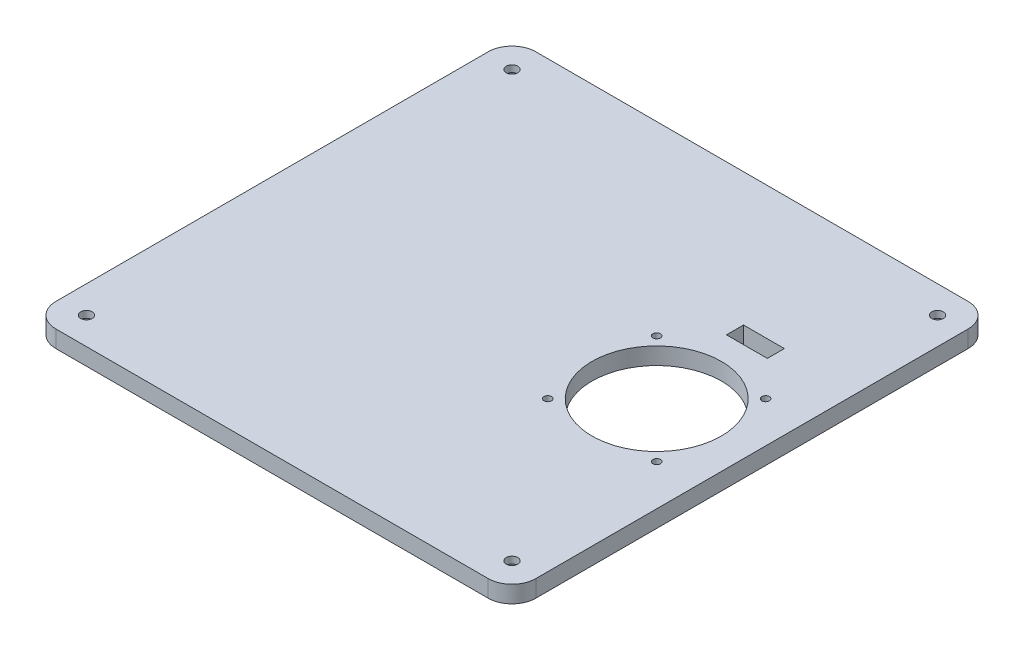
SolidWorks part; units mm, degrees
ref_plane "Front Plane" through (0, 0, 0) normal (0, 0, 1) x (1, 0, 0)
ref_plane "Top Plane" through (0, 0, 0) normal (0, 1, 0) x (1, 0, 0)
ref_plane "Right Plane" through (0, 0, 0) normal (1, 0, 0) x (0, 0, -1)
sketch "Sketch1" plane through (0, 0, 0) normal (0, 1, 0) x (1, 0, 0)
  line L1 (-70.5, 70.5) -> (70.5, 70.5)
  line L2 (-70.5, 70.5) -> (-70.5, -70.5)
  line L3 (-70.5, -70.5) -> (70.5, -70.5)
  line L4 (70.5, 70.5) -> (70.5, -70.5)
  line L5 (0, -70.5) -> (0, 70.5) construction
  line L6 (-70.5, 0) -> (70.5, 0) construction
  point P0 (0, 0)
  dimension "D1" = 141
  dimension "D2" = 141
extrude "Boss-Extrude1" add sketch "Sketch1" along normal blind 5
sketch "Sketch3" plane through (0, 5, 0) normal (0, 1, 0) x (1, 0, 0)
  line L1 (26.5, 16) -> (58.5, 16) construction
  line L2 (26.5, 16) -> (26.5, -16) construction
  line L3 (26.5, -16) -> (58.5, -16) construction
  line L4 (58.5, 16) -> (58.5, -16) construction
  line L5 (70.5, -70.5) -> (70.5, 70.5) construction
  circle A0 centre (26.5, 16) radius 1.1
  circle A1 centre (58.5, 16) radius 1.1
  circle A2 centre (58.5, -16) radius 1.1
  circle A3 centre (26.5, -16) radius 1.1
  point P8 (26.5, 0)
  dimension "D1" = 2.2
  dimension "D2" = 32
  dimension "D3" = 32
  dimension "D4" = 12
extrude "Cut-Extrude1" cut sketch "Sketch3" against normal up to next
hole_wizard "CBORE for M3 SHCS1" positions "3DSketch1" profile "Sketch8" counterbore size "M3" standard "ANSI Metric" end condition through all
sketch3d "3DSketch1"
  line L0 (-70.5, 0, -70.5) -> (-70.5, 0, 70.5) construction
  line L1 (-70.5, 0, 70.5) -> (70.5, 0, 70.5) construction
  point P15 (-62.5, 0, 62.5)
  point P22 (-62.5, 0, -62.5)
  point P25 (62.5, 0, -62.5)
  point P26 (62.5, 0, 62.5)
  dimension "D1" = 8
  dimension "D2" = 8
sketch "Sketch8" plane through (-62.5, 0, 62.5) normal (1, 0, 0) x (0, 0, -1)
  line L0 (0, 0) -> (0, 5)
  line L1 (0, 5) -> (1.7, 5)
  line L3 (1.7, 5) -> (1.7, 3)
  line L4 (1.7, 3) -> (3.25, 3)
  line L5 (3.25, 3) -> (3.25, 0)
  line L7 (3.25, 0) -> (0, 0)
  line L11 (0, -6.35) -> (0, 107.95) construction
  dimension "Thru Hole Dia." = 3.4
  dimension "Thru Hole Depth" = 5
  dimension "C'Bore Dia." = 6.5
  dimension "C'Bore Depth" = 3
fillet "Fillet1" radius 7 4 edges at (-70.5, 2.5, -70.5) (70.5, 2.5, -70.5) (70.5, 2.5, 70.5) (-70.5, 2.5, 70.5)
sketch "Esquisse1" plane through (0, 0, 0) normal (0, -1, 0) x (1, 0, 0)
  line L0 (58.5, 16) -> (26.5, -16) construction
  circle A1 centre (42.5, 0) radius 19
  dimension "D1" = 38
extrude "Enlèv. mat.-Extru.1" cut sketch "Esquisse1" against normal through all
sketch "Esquisse2" plane through (0, 0, 0) normal (0, -1, 0) x (1, 0, 0)
  line L0 (42.5, -19) -> (42.5, -29) construction
  line L2 (48.5, -26.5) -> (36.5, -26.5)
  line L3 (48.5, -26.5) -> (48.5, -31.5)
  line L4 (48.5, -31.5) -> (36.5, -31.5)
  line L5 (36.5, -26.5) -> (36.5, -31.5)
  line L6 (48.5, -26.5) -> (36.5, -31.5) construction
  line L7 (48.5, -31.5) -> (36.5, -26.5) construction
  circle A0 centre (42.5, 0) radius 19 construction
  dimension "D1" = 5
  dimension "D2" = 12
  dimension "D3" = 10
extrude "Enlèv. mat.-Extru.2" cut sketch "Esquisse2" against normal through all
